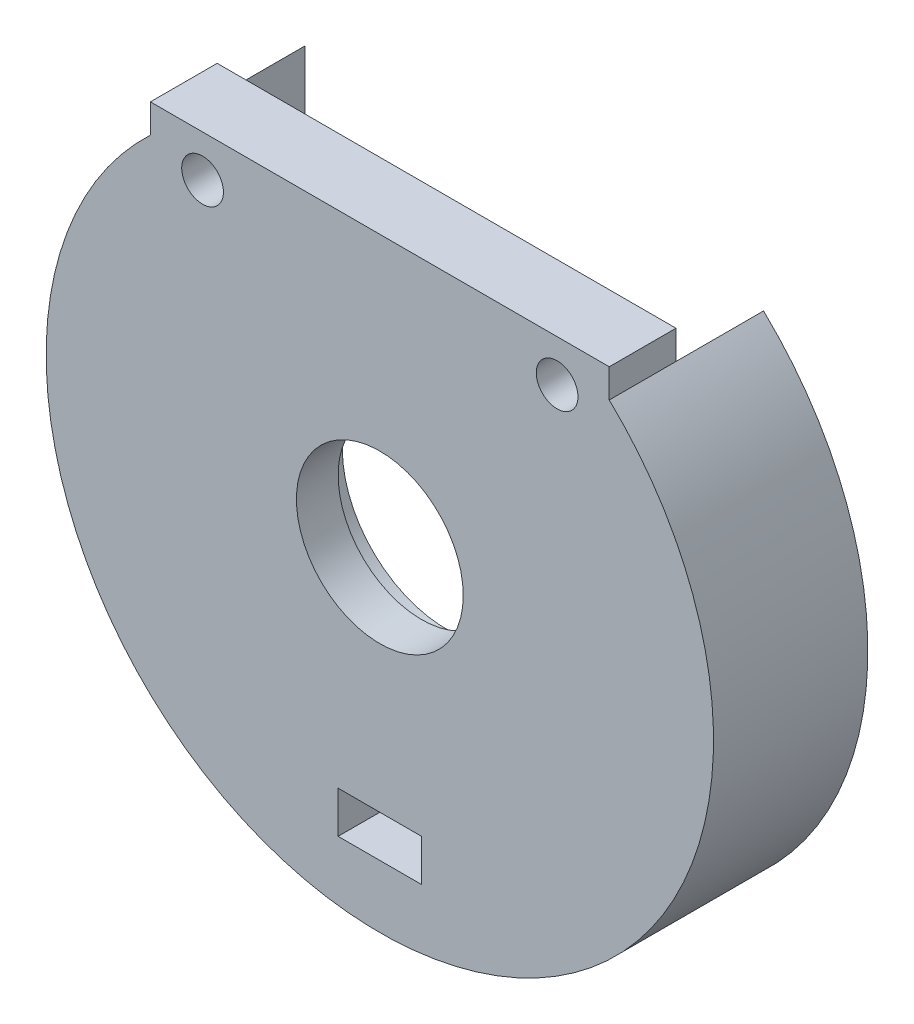
SolidWorks part; units mm, degrees
ref_plane "Front Plane" through (0, 0, 0) normal (0, 0, 1) x (1, 0, 0)
ref_plane "Top Plane" through (0, 0, 0) normal (0, 1, 0) x (1, 0, 0)
ref_plane "Right Plane" through (0, 0, 0) normal (1, 0, 0) x (0, 0, -1)
sketch "Sketch1" plane through (0, 0, 0) normal (0, 0, 1) x (1, 0, 0)
  line L0 (-5.5, 5.8095) -> (-5.5, -2.5)
  line L1 (-5.5, -2.5) -> (-2.5, -5.5)
  line L2 (-2.5, -5.5) -> (2.5, -5.5)
  line L3 (2.5, -5.5) -> (5.5, -2.5)
  line L4 (5.5, -2.5) -> (5.5, 5.8095)
  line L5 (5.5, 6.5) -> (4.6637, 6.5) construction
  line L6 (-5.5, 6.5) -> (-5.5, 5.8095) construction
  line L7 (-4.6637, 6.5) -> (-5.5, 6.5) construction
  line L8 (4.6637, 6.5) -> (-4.6637, 6.5) construction
  line L9 (5.5, 5.8095) -> (5.5, 6.5) construction
  arc A0 (-5.5, 5.8095) -> (5.5, 5.8095) centre (0, 0) ccw
  arc A1 (-4.6637, 6.5) -> (-5.5, 5.8095) centre (0, 0) ccw construction
  arc A2 (4.6637, 6.5) -> (-4.6637, 6.5) centre (0, 0) ccw construction
  arc A3 (5.5, 5.8095) -> (4.6637, 6.5) centre (0, 0) ccw construction
  dimension "D1" = 16
extrude "Boss-Extrude1" add sketch "Sketch1" along normal blind 1.4
sketch "Sketch2" plane through (0, 0, 1.4) normal (0, 0, 1) x (1, 0, 0)
  line L0 (1, -5.5) -> (-1, -5.5) construction
  line L1 (2.5, -5.5) -> (-2.5, -5.5) construction
  line L2 (-1, -5.5) -> (-1, -6.5)
  line L3 (-1, -6.5) -> (1, -6.5)
  line L4 (1, -6.5) -> (1, -5.5)
  line L5 (-5.5, -2.5) -> (-5.5, 5.8095)
  line L6 (-5.5, -2.5) -> (-2.5, -5.5)
  line L7 (-2.5, -5.5) -> (-5.5, -2.5) construction
  line L8 (-2.5, -5.5) -> (-1, -5.5)
  line L9 (2.5, -5.5) -> (5.5, -2.5)
  line L10 (5.5, -2.5) -> (5.5, 5.8095)
  line L11 (5.5, 5.8095) -> (5.5, -2.5) construction
  line L12 (1, -5.5) -> (2.5, -5.5)
  line L13 (-1, -5.5) -> (1, -5.5) construction
  arc A0 (-5.5, 5.8095) -> (5.5, 5.8095) centre (0, 0) ccw
  arc A1 (5.5, 5.8095) -> (-5.5, 5.8095) centre (0, 0) ccw construction
  point P5 (0, -5.5)
  dimension "D1" = 2
  dimension "D2" = 1
extrude "Boss-Extrude2" add sketch "Sketch2" along normal up to surface (0.7 mm away)
sketch "Sketch3" plane through (0, 0, 2.1) normal (0, 0, 1) x (1, 0, 0)
  line L1 (-1, -5.5) -> (-1, -6.5)
  line L2 (-1, -6.5) -> (1, -6.5)
  line L3 (1, -6.5) -> (1, -5.5)
  line L4 (1, -5.5) -> (-1, -5.5)
  line L6 (-5.5, 5.8095) -> (-5.5, 6.5)
  line L7 (-5.5, 6.5) -> (5.5, 6.5)
  line L8 (5.5, 6.5) -> (5.5, 5.8095)
  circle A0 centre (0, 0) radius 2.5
  circle A1 centre (-4.25, 5.5) radius 0.5
  circle A2 centre (4.25, 5.5) radius 0.5
  arc A3 (-5.5, 5.8095) -> (5.5, 5.8095) centre (0, 0) ccw
  arc A4 (-5.5, 5.8095) -> (5.5, 5.8095) centre (0, 0) ccw construction
  circle M1 centre (-4.25, 5.5) radius 0.5
  circle M2 centre (4.25, 5.5) radius 0.5
  line M3 (5.5, -2.5) -> (5.5, 6.5)
  line M4 (5.5, 6.5) -> (-5.5, 6.5)
  line M5 (-5.5, 6.5) -> (-5.5, -2.5)
  line M6 (-5.5, -2.5) -> (-2.5, -5.5)
  line M7 (-2.5, -5.5) -> (2.5, -5.5)
  line M8 (2.5, -5.5) -> (5.5, -2.5)
  circle M9 centre (0, 0) radius 2.5
  dimension "D1" = 5
  dimension "D2" = 1
extrude "Boss-Extrude3" add sketch "Sketch3" along normal up to surface (0.6 mm away) contours M8 M3 M4 M5 M6 M7 M2 M9 M1 | A3 L3 L2 L1 M5 M3 M8 M7 M6
sketch "Sketch4" plane through (0, 0, 2.7) normal (0, 0, 1) x (1, 0, 0)
  line L0 (-1, -5.5) -> (-1, -6.5)
  line L1 (-1, -6.5) -> (1, -6.5)
  line L2 (1, -6.5) -> (1, -5.5)
  line L3 (1, -5.5) -> (-1, -5.5)
  line L4 (-5.5, 5.8095) -> (-5.5, 6.5)
  line L5 (-5.5, 6.5) -> (5.5, 6.5)
  line L6 (5.5, 6.5) -> (5.5, 5.8095)
  circle A0 centre (0, 0) radius 2
  circle A1 centre (-4.25, 5.5) radius 0.5
  circle A2 centre (4.25, 5.5) radius 0.5
  arc A3 (-5.5, 5.8095) -> (5.5, 5.8095) centre (0, 0) ccw
  arc A4 (-4.6637, 6.5) -> (-5.5, 5.8095) centre (0, 0) ccw construction
  arc A5 (4.6637, 6.5) -> (-4.6637, 6.5) centre (0, 0) ccw construction
  arc A6 (5.5, 5.8095) -> (4.6637, 6.5) centre (0, 0) ccw construction
  dimension "D1" = 4
extrude "Boss-Extrude4" add sketch "Sketch4" along normal blind 1
